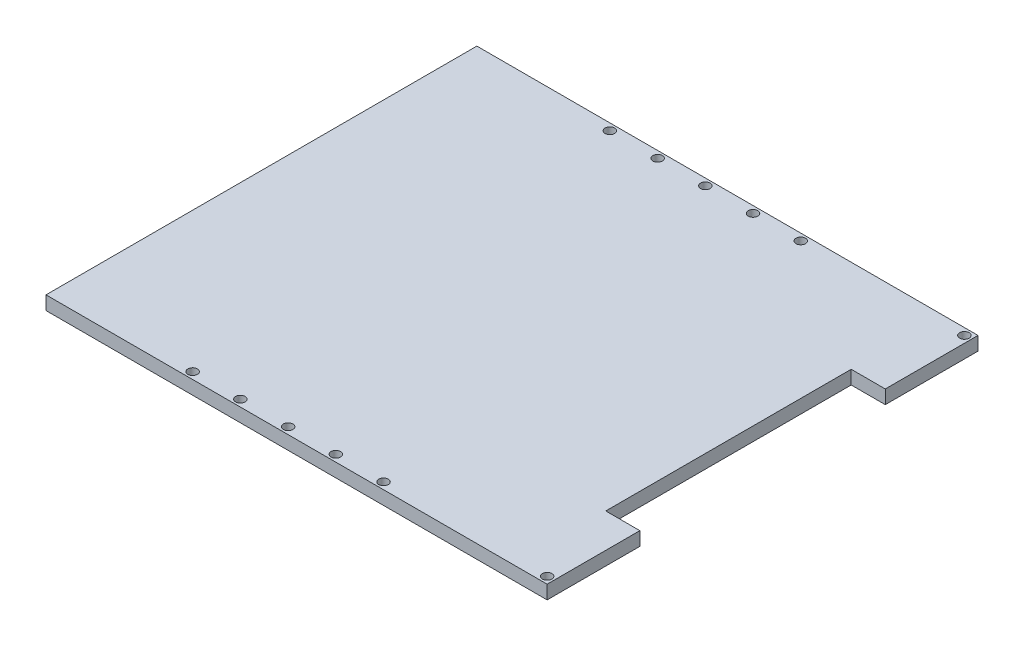
SolidWorks part; units mm, degrees
ref_plane "Front Plane" through (0, 0, 0) normal (0, 0, 1) x (1, 0, 0)
ref_plane "Top Plane" through (0, 0, 0) normal (0, 1, 0) x (1, 0, 0)
ref_plane "Right Plane" through (0, 0, 0) normal (1, 0, 0) x (0, 0, -1)
sketch "Sketch1" plane through (0, 0, 0) normal (0, 1, 0) x (1, 0, 0)
  line L1 (-91.885, -79) -> (91.885, -79)
  line L2 (-91.885, -79) -> (-91.885, 79)
  line L3 (-91.885, 79) -> (91.885, 79)
  line L4 (91.885, -79) -> (91.885, 79)
  line L5 (-91.885, -79) -> (91.885, 79) construction
  line L6 (-91.885, 79) -> (91.885, -79) construction
  circle A0 centre (89.385, 76.5) radius 1.75
  circle A1 centre (29.385, 76.5) radius 1.75
  circle A2 centre (11.885, 76.5) radius 1.75
  circle A3 centre (-5.615, 76.5) radius 1.75
  circle A4 centre (-23.115, 76.5) radius 1.75
  circle A5 centre (-40.615, 76.5) radius 1.75
  circle A6 centre (89.385, -76.5) radius 1.75
  circle A7 centre (29.385, -76.5) radius 1.75
  circle A8 centre (11.885, -76.5) radius 1.75
  circle A9 centre (-5.615, -76.5) radius 1.75
  circle A10 centre (-23.115, -76.5) radius 1.75
  circle A11 centre (-40.615, -76.5) radius 1.75
  point P0 (0, 0)
  dimension "D3" = 3.5
  dimension "D1" = 183.77
  dimension "D2" = 158
  dimension "D4" = 2.5
  dimension "D5" = 2.5
  dimension "D6" = 2
  dimension "D7" = 5
  dimension "D8" = 2
extrude "Boss-Extrude1" add sketch "Sketch1" along normal blind 5
sketch "Sketch2" plane through (0, 5, 0) normal (0, 1, 0) x (1, 0, 0)
  line L0 (91.885, -79) -> (91.885, 79) construction
  line L1 (104.385, -45) -> (79.385, -45)
  line L2 (104.385, -45) -> (104.385, 45)
  line L3 (104.385, 45) -> (79.385, 45)
  line L4 (79.385, -45) -> (79.385, 45)
  line L5 (104.385, -45) -> (79.385, 45) construction
  line L6 (104.385, 45) -> (79.385, -45) construction
  point P0 (91.885, 0)
  dimension "D1" = 25
  dimension "D2" = 90
extrude "Cut-Extrude1" cut sketch "Sketch2" against normal blind 10
